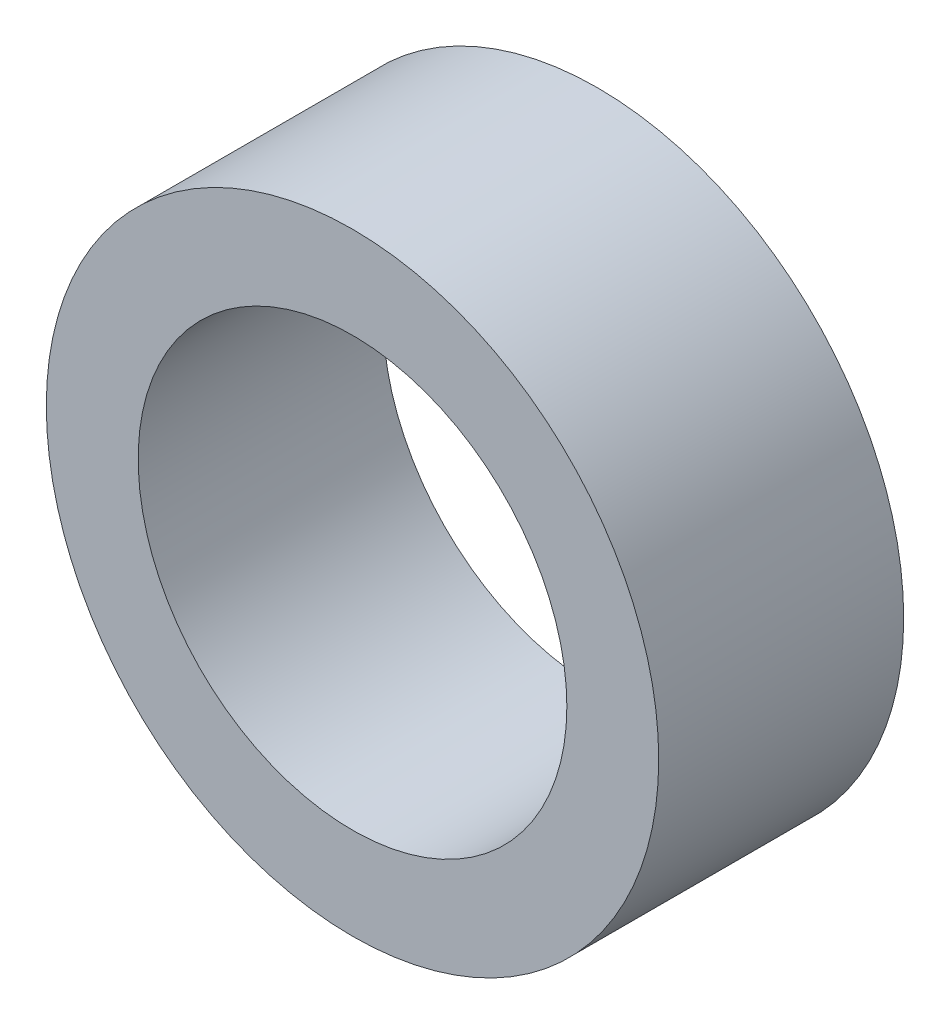
SolidWorks part; units mm, degrees
ref_plane "Front Plane" through (0, 0, 0) normal (0, 0, 1) x (1, 0, 0)
ref_plane "Top Plane" through (0, 0, 0) normal (0, 1, 0) x (1, 0, 0)
ref_plane "Right Plane" through (0, 0, 0) normal (1, 0, 0) x (0, 0, -1)
sketch "Sketch1" plane through (0, 0, 0) normal (0, 0, 1) x (1, 0, 0)
  circle A0 centre (0, 0) radius 25
  circle A1 centre (0, 0) radius 17.5
  dimension "D1" = 35
  dimension "D2" = 50
extrude "Boss-Extrude1" add sketch "Sketch1" along normal blind 20
